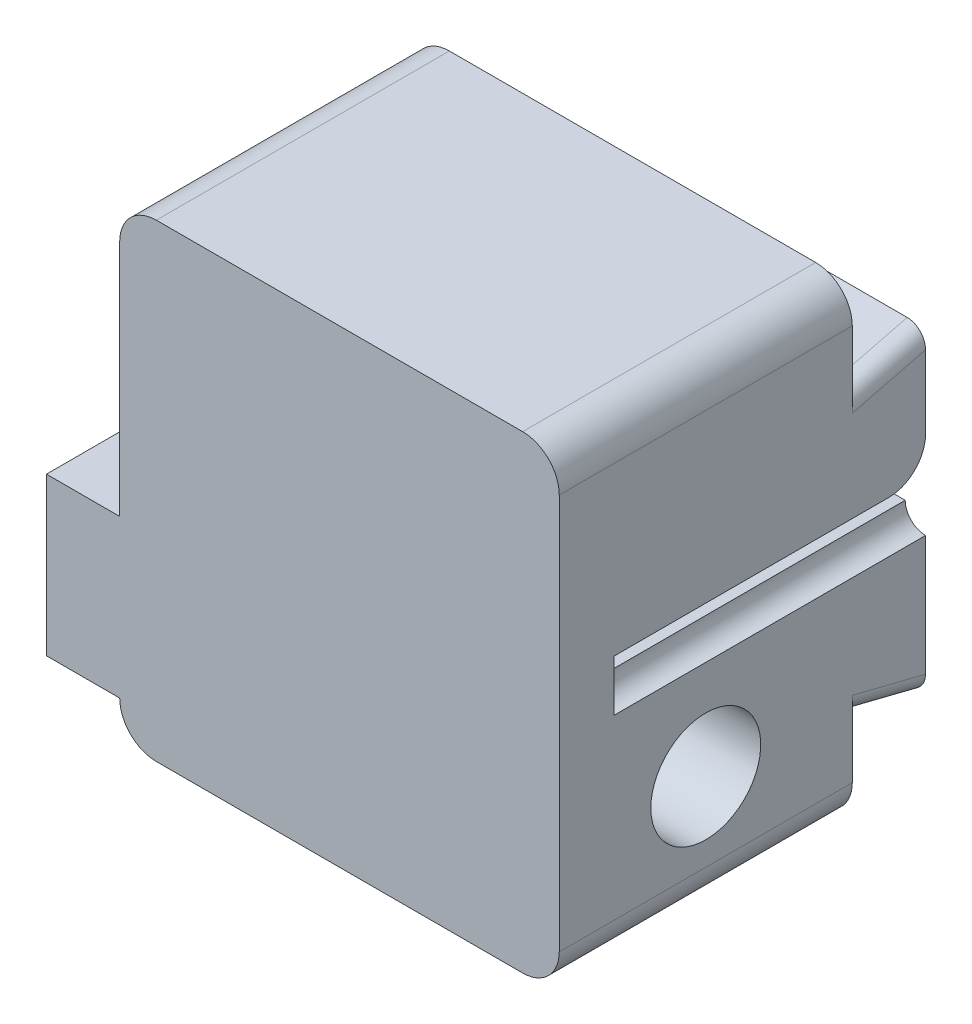
SolidWorks part; units mm, degrees
material "PC High Viscosity"
ref_plane "Front Plane" through (0, 0, 0) normal (0, 0, 1) x (1, 0, 0)
ref_plane "Top Plane" through (0, 0, 0) normal (0, 1, 0) x (1, 0, 0)
ref_plane "Right Plane" through (0, 0, 0) normal (1, 0, 0) x (0, 0, -1)
sketch "Sketch4" plane through (0, 0, 0) normal (0, 0, 1) x (1, 0, 0)
  line L1 (1, 0.1) -> (11, 0.1)
  line L2 (0, 1.1) -> (0, 11.9)
  line L3 (1, 12.9) -> (11, 12.9)
  line L4 (12, 1.1) -> (12, 11.9)
  arc A0 (11, 12.9) -> (12, 11.9) centre (11, 11.9) cw
  arc A1 (11, 0.1) -> (12, 1.1) centre (11, 1.1) ccw
  arc A3 (0, 11.9) -> (1, 12.9) centre (1, 11.9) cw
  arc A4 (1, 0.1) -> (0, 1.1) centre (1, 1.1) cw
extrude "Boss-Extrude1" add sketch "Sketch4" along normal blind 10
sketch "Sketch5" plane through (0, 0, 0) normal (0, 0, 1) x (1, 0, 0)
  line L0 (11.445, 6.5) -> (10.555, 6.5)
  line L1 (9.445, 6.5) -> (8.555, 6.5)
  line L2 (7.445, 6.5) -> (6.555, 6.5)
  line L3 (5.445, 6.5) -> (4.555, 6.5)
  line L4 (0, 7.345) -> (12, 7.345)
  line L5 (12, 7.345) -> (12, 5.945)
  line L6 (0, 7.345) -> (0, 5.945)
  line L7 (3.445, 6.5) -> (2.555, 6.5)
  line L8 (1.445, 6.5) -> (0.555, 6.5)
  arc A0 (9.445, 6.5) -> (10.555, 6.5) centre (10, 6.5) ccw
  arc A1 (11.445, 6.5) -> (12, 5.945) centre (12, 6.5) ccw
  arc A2 (7.445, 6.5) -> (8.555, 6.5) centre (8, 6.5) ccw
  arc A3 (6.555, 6.5) -> (5.445, 6.5) centre (6, 6.5) cw
  arc A4 (4.555, 6.5) -> (3.445, 6.5) centre (4, 6.5) cw
  arc A5 (1.445, 6.5) -> (2.555, 6.5) centre (2, 6.5) ccw
  arc A6 (0.555, 6.5) -> (0, 5.945) centre (0, 6.5) cw
extrude "Cut-Extrude1" cut sketch "Sketch5" along normal blind 8.5
sketch "Sketch6" plane through (0, 0, 0) normal (-1, 0, 0) x (0, 0, 1)
  line L1 (2, 2.65) -> (2, 0.1)
  line L12 (0, 12.9) -> (0, 10.85)
  line L13 (2, 10.35) -> (2, 12.9)
  line L14 (2, 12.9) -> (0, 12.9)
  line L15 (0, 10.85) -> (2, 10.35)
  line L16 (2, 2.65) -> (0, 2.15)
  line L17 (10, 0.1) -> (0, 0.1) construction
  line L18 (2, 0.1) -> (0, 0.1)
  line L19 (0, 0.1) -> (0, 2.15)
  circle A0 centre (6, 3.25) radius 1.5
extrude "Cut-Extrude2" cut sketch "Sketch6" against normal up to surface (12 mm away)
sketch "Sketch7" plane through (0, 0, 0) normal (-1, 0, 0) x (0, 0, 1)
  line L10 (7.8764, 1.1) -> (9.1177, 3.25)
  line L11 (9.1177, 3.25) -> (7.8793, 5.395)
  line L14 (2, 1.1) -> (2, 5.395)
  line L16 (4.1207, 5.395) -> (2.8823, 3.25)
  line L17 (2.8823, 3.25) -> (4.1236, 1.1)
  line L26 (10, 1.1) -> (7.8764, 1.1)
  line L27 (4.1207, 5.395) -> (2, 5.395)
  line L28 (10, 5.395) -> (7.8793, 5.395)
  line L29 (10, 5.395) -> (10, 1.1)
  line L30 (4.1236, 1.1) -> (2, 1.1)
extrude "Boss-Extrude2" add sketch "Sketch7" along normal blind 2
fillet "Fillet2" radius 0.5 4 edges at (0, 2.4, 1) (0, 10.6, 1) (12, 10.6, 1) (12, 2.4, 1)
fillet "Fillet3" radius 1 1 edges at (6, 7.345, 0)
